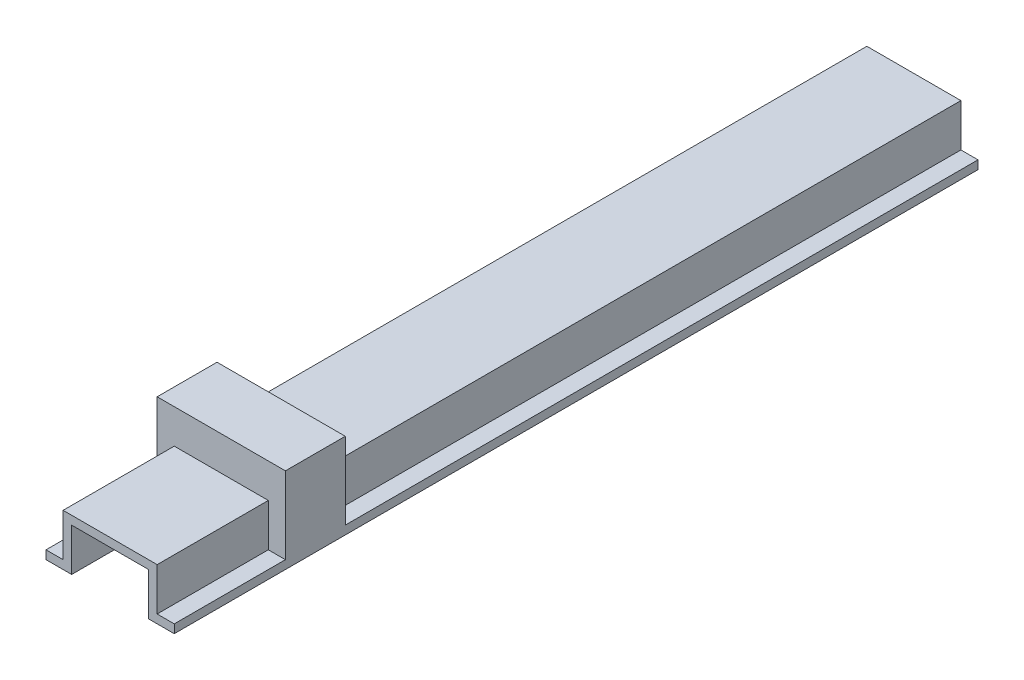
SolidWorks part; units mm, degrees
ref_plane "Front Plane" through (0, 0, 0) normal (0, 0, 1) x (1, 0, 0)
ref_plane "Top Plane" through (0, 0, 0) normal (0, 1, 0) x (1, 0, 0)
ref_plane "Right Plane" through (0, 0, 0) normal (1, 0, 0) x (0, 0, -1)
sketch "Sketch1" plane through (0, 0, 0) normal (0, 0, 1) x (1, 0, 0)
  line L0 (-5.366, -2.186) -> (-7.366, -2.186)
  line L1 (-4.366, 1.814) -> (4.634, 1.814)
  line L2 (-4.366, 1.814) -> (-4.366, -2.186)
  line L3 (7.634, -2.186) -> (5.634, -2.186)
  line L4 (4.634, 1.814) -> (4.634, -2.186)
  line L7 (-5.366, 2.814) -> (5.634, 2.814)
  line L8 (-5.366, 2.814) -> (-5.366, -2.186)
  line L9 (-4.366, -2.186) -> (-4.366, -3.186)
  line L10 (5.634, 2.814) -> (5.634, -2.186)
  line L11 (-4.366, -3.186) -> (-7.366, -3.186)
  line L12 (-7.366, -2.186) -> (-7.366, -3.186)
  line L14 (4.634, -2.186) -> (4.634, -3.186)
  line L15 (4.634, -3.186) -> (7.634, -3.186)
  line L16 (7.634, -2.186) -> (7.634, -3.186)
  point P0 (0, 0)
  point P6 (0.134, -0.0632)
  dimension "D1" = 9
  dimension "D2" = 4
  dimension "D3" = 11
  dimension "D4" = 5
  dimension "D5" = 1
  dimension "D6" = 1
  dimension "D7" = 3
  dimension "D8" = 3
  dimension "D9" = 1
  dimension "D10" = 1
  dimension "D11" = 1
  dimension "D12" = 1
  dimension "D13" = 5
  dimension "D14" = 4
extrude "Boss-Extrude1" add sketch "Sketch1" along normal blind 94
sketch "Sketch2" plane through (0, -2.186, 0) normal (0, 1, 0) x (1, 0, 0)
  line L0 (7.634, -94) -> (7.634, 0) construction
  line L1 (-7.366, -74) -> (7.634, -74)
  line L2 (-7.366, -74) -> (-7.366, -81)
  line L3 (-7.366, -81) -> (7.634, -81)
  line L4 (7.634, -74) -> (7.634, -81)
  line L5 (-7.366, -74) -> (7.634, -81) construction
  line L6 (-7.366, -81) -> (7.634, -74) construction
  line L7 (-7.366, -94) -> (-4.366, -94) construction
  point P0 (0.134, -77.5)
  dimension "D1" = 15
  dimension "D2" = 13
  dimension "D3" = 7
extrude "Boss-Extrude2" add sketch "Sketch2" along normal blind 9
sketch "Sketch3" plane through (0, -2.186, 0) normal (0, -1, 0) x (1, 0, 0)
  line L1 (-4.366, 74) -> (4.634, 74)
  line L2 (-4.366, 74) -> (-4.366, 81)
  line L3 (-4.366, 81) -> (4.634, 81)
  line L4 (4.634, 74) -> (4.634, 81)
extrude "Cut-Extrude1" cut sketch "Sketch3" against normal blind 4
sketch "Sketch4" plane through (-7.366, 0, 0) normal (-1, 0, 0) x (0, 0, 1)
  line L0 (81, 6.814) -> (81, -2.186) construction
  line L1 (75, 5.814) -> (80, 5.814)
  line L2 (75, 5.814) -> (75, -1.186)
  line L3 (75, -1.186) -> (80, -1.186)
  line L4 (80, 5.814) -> (80, -1.186)
  line L5 (74, 6.814) -> (74, -2.186) construction
  line L6 (74, 6.814) -> (81, 6.814) construction
  dimension "D1" = 1
  dimension "D2" = 1
  dimension "D3" = 1
  dimension "D4" = 7
extrude "Cut-Extrude2" cut sketch "Sketch4" against normal blind 12
